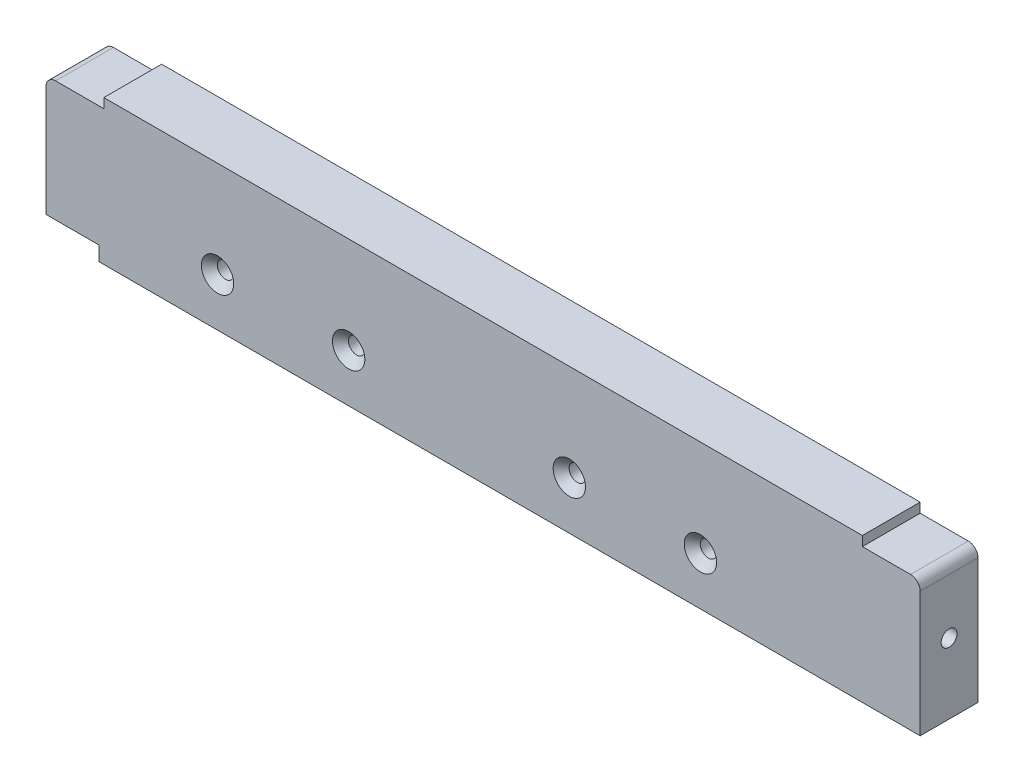
SolidWorks part; units mm, degrees
material "PVC Rígido"
ref_plane "Plano frontal" through (0, 0, 0) normal (0, 0, 1) x (1, 0, 0)
ref_plane "Plano superior" through (0, 0, 0) normal (0, 1, 0) x (1, 0, 0)
ref_plane "Plano direito" through (0, 0, 0) normal (1, 0, 0) x (0, 0, -1)
sketch "Esboço1" plane through (0, 0, 0) normal (0, 0, 1) x (1, 0, 0)
  line L1 (-62.8194, 199.9278) -> (56.1806, 199.9278)
  line L2 (-62.8194, 199.9278) -> (-62.8194, 169.9278)
  line L3 (-62.8194, 169.9278) -> (56.1806, 169.9278)
  line L4 (56.1806, 199.9278) -> (56.1806, 169.9278)
  dimension "D1" = 30
extrude "Ressalto-extrusão1" add sketch "Esboço1" along normal blind 12
hole_wizard "Escareado para SFHCS M31" positions "Esboço5" profile "Esboço4" countersink size "M3" standard "Métrico Ansi" end condition through all
sketch "Esboço5" plane through (0, 0, 12) normal (0, 0, 1) x (1, 0, 0)
  line L0 (-62.8194, 199.9278) -> (-62.8194, 169.9278) construction
  line L1 (56.1806, 169.9278) -> (56.1806, 199.9278) construction
  line L2 (-62.8194, 169.9278) -> (56.1806, 169.9278) construction
  point P0 (46.7806, 179.9278)
  point P1 (-53.4194, 179.9278)
  point P10 (-26.2194, 179.9278)
  point P12 (19.5806, 179.9278)
  dimension "D1" = 9.4
  dimension "D2" = 9.4
  dimension "D3" = 10
  dimension "D4" = 10
  dimension "D5" = 10
  dimension "D6" = 10
  dimension "D7" = 36.6
  dimension "D8" = 36.6
sketch "Esboço4" plane through (46.7806, 179.9278, 12) normal (1, 0, 0) x (0, -1, 0)
  line L0 (0, 0) -> (0, 12)
  line L1 (0, 12) -> (1.7, 12)
  line L2 (1.7, 12) -> (1.7, 1.66)
  line L3 (1.7, 1.66) -> (3.36, 0)
  line L5 (3.36, 0) -> (0, 0)
  line L6 (-1.7, 1.66) -> (-3.36, 0) construction
  line L11 (0, -6.35) -> (0, 107.95) construction
  dimension "Thru Hole Dia." = 3.4
  dimension "Thru Hole Depth" = 12
  dimension "Near C'Sink Dia." = 6.72
  dimension "Near C'Sink Angle" = 90
sketch "Esboço8" plane through (0, 0, 12) normal (0, 0, 1) x (1, 0, 0)
  line L1 (-89.0194, 199.9278) -> (-62.8194, 199.9278)
  line L2 (-89.0194, 199.9278) -> (-89.0194, 169.9278)
  line L3 (-89.0194, 169.9278) -> (-62.8194, 169.9278)
  line L4 (-62.8194, 199.9278) -> (-62.8194, 169.9278)
  dimension "D1" = 26.2
extrude "Ressalto-extrusão2" add sketch "Esboço8" against normal blind 12
sketch "Esboço9" plane through (0, 0, 0) normal (0, 0, 1) x (1, 0, 0)
  line L1 (92.3806, 199.9278) -> (56.1806, 199.9278)
  line L2 (92.3806, 199.9278) -> (92.3806, 169.9278)
  line L3 (92.3806, 169.9278) -> (56.1806, 169.9278)
  line L4 (56.1806, 199.9278) -> (56.1806, 169.9278)
  dimension "D1" = 36.2
extrude "Ressalto-extrusão3" add sketch "Esboço9" along normal blind 12
sketch "Esboço10" plane through (0, 199.9278, 0) normal (0, 1, 0) x (1, 0, 0)
  line L0 (92.3806, -12) -> (-89.0194, -12) construction
  line L1 (-89.0194, 0) -> (-77.0194, 0)
  line L2 (-89.0194, 0) -> (-89.0194, -12)
  line L3 (-89.0194, -12) -> (-77.0194, -12)
  line L4 (-77.0194, 0) -> (-77.0194, -12)
  dimension "D1" = 12
extrude "Corte-extrusão1" cut sketch "Esboço10" against normal blind 2
fillet "Filete1" radius 2 1 edges at (-89.0194, 197.9278, 6)
sketch "Esboço12" plane through (0, 169.9278, 0) normal (0, -1, 0) x (1, 0, 0)
  line L0 (-89.0194, 12) -> (92.3806, 12) construction
  line L1 (-89.0194, 0) -> (-78.0194, 0)
  line L2 (-89.0194, 0) -> (-89.0194, 12)
  line L3 (-89.0194, 12) -> (-78.0194, 12)
  line L4 (-78.0194, 0) -> (-78.0194, 12)
  dimension "D1" = 11
extrude "Corte-extrusão2" cut sketch "Esboço12" against normal blind 3
hole_wizard "Broca de rosquear para tarraxa de M4x0.71" positions "Esboço14" profile "Esboço13" hole size "M4x0.7" standard "Métrico Ansi"
sketch "Esboço14" plane through (-89.0194, 0, 0) normal (-1, 0, 0) x (0, 0, 1)
  line L0 (12, 172.9278) -> (0, 172.9278) construction
  line L1 (12, 195.9278) -> (12, 172.9278) construction
  point P0 (6, 184.6778)
  dimension "D1" = 11.75
  dimension "D2" = 6
sketch "Esboço13" plane through (-89.0194, 184.6778, 6) normal (0, 1, 0) x (0, 0, 1)
  line L0 (0, 0) -> (0, 10.9914)
  line L1 (0, 10.9914) -> (1.65, 10)
  line L2 (1.65, 10) -> (1.65, 0)
  line L5 (1.65, 0) -> (0, 0)
  line L10 (0, 10.9914) -> (-1.65, 10) construction
  line L11 (0, -6.35) -> (0, 107.95) construction
  dimension "Hole Dia." = 3.3
  dimension "Hole Depth" = 10
  dimension "Drill Angle" = 118
cosmetic thread "Representação de rosca1" parameters "D2"=4
sketch "Esboço15" plane through (0, 199.9278, 0) normal (0, 1, 0) x (-1, 0, 0)
  line L0 (-92.3806, 0) -> (77.0194, 0) construction
  line L1 (-92.3806, 0) -> (-80.3806, 0)
  line L2 (-92.3806, 0) -> (-92.3806, 12)
  line L3 (-92.3806, 12) -> (-80.3806, 12)
  line L4 (-80.3806, 0) -> (-80.3806, 12)
  line L5 (-92.3806, 12) -> (77.0194, 12) construction
  dimension "D1" = 12
extrude "Corte-extrusão3" cut sketch "Esboço15" against normal blind 2
fillet "Filete2" radius 2 1 edges at (92.3806, 197.9278, 6)
hole_wizard "Broca de rosquear para tarraxa de M4x0.72" positions "Esboço17" profile "Esboço16" hole size "M4x0.7" standard "Métrico Ansi"
sketch "Esboço17" plane through (92.3806, 0, 0) normal (1, 0, 0) x (0, 0, -1)
  line L0 (-12, 169.9278) -> (-12, 195.9278) construction
  line L1 (-12.0412, 172.7363) -> (135.9588, 172.7363) construction
  point P0 (-6, 184.4863)
  dimension "D1" = 6
  dimension "D2" = 11.75
sketch "Esboço16" plane through (92.3806, 184.4863, 6) normal (0, 1, 0) x (0, 0, -1)
  line L0 (0, 0) -> (0, 10.9914)
  line L1 (0, 10.9914) -> (1.65, 10)
  line L2 (1.65, 10) -> (1.65, 0)
  line L5 (1.65, 0) -> (0, 0)
  line L10 (0, 10.9914) -> (-1.65, 10) construction
  line L11 (0, -6.35) -> (0, 107.95) construction
  dimension "Hole Dia." = 3.3
  dimension "Hole Depth" = 10
  dimension "Drill Angle" = 118
cosmetic thread "Representação de rosca2" parameters "D2"=4
